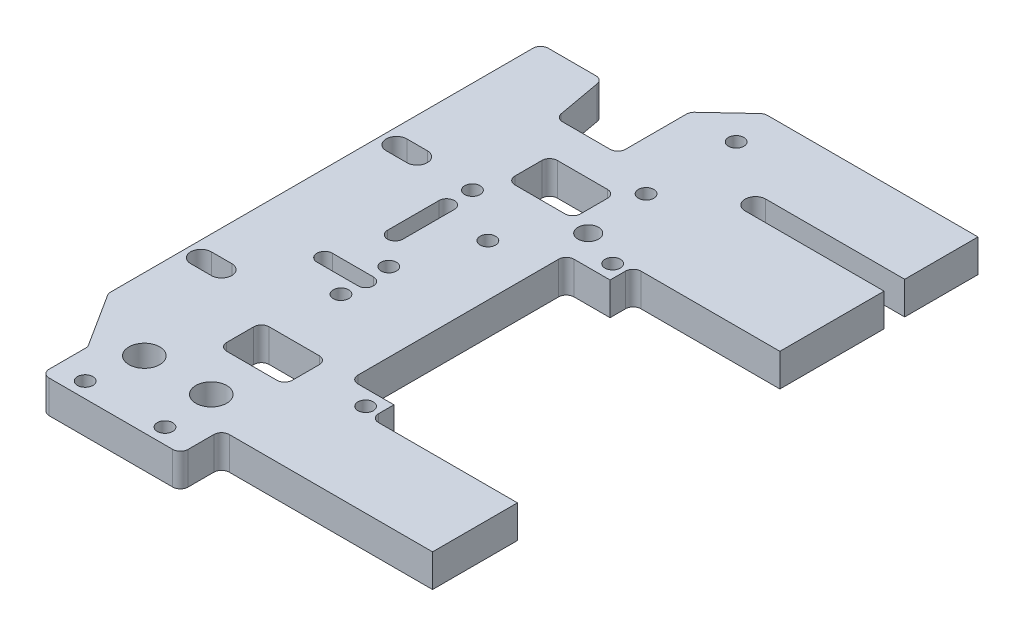
SolidWorks part; units mm, degrees
material "1060 Alloy"
ref_plane "Front Plane" through (0, 0, 0) normal (0, 0, 1) x (1, 0, 0)
ref_plane "Top Plane" through (0, 0, 0) normal (0, 1, 0) x (1, 0, 0)
ref_plane "Right Plane" through (0, 0, 0) normal (1, 0, 0) x (0, 0, -1)
sketch "Sketch1" plane through (0, 0, 0) normal (0, 1, 0) x (1, 0, 0)
  line L0 (48, 228) -> (48, 71.7384) construction
  line L2 (0, 20) -> (0, 104)
  line L4 (96, 20) -> (96, 104)
  line L5 (33.5, 114) -> (26, 107)
  line L6 (26, 107) -> (26, 93)
  line L7 (26, 93) -> (14, 93)
  line L8 (14, 93) -> (12, 104)
  line L9 (12, 104) -> (0, 104)
  line L10 (62.5, 114) -> (70, 107)
  line L11 (70, 107) -> (70, 93)
  line L12 (70, 93) -> (82, 93)
  line L13 (82, 93) -> (84, 104)
  line L14 (84, 104) -> (96, 104)
  line L15 (33.5, 114) -> (62.5, 114)
  line L16 (0, 20) -> (7, 9)
  line L17 (7, 9) -> (7, 0)
  line L18 (89, 9) -> (89, 0)
  line L19 (96, 20) -> (89, 9)
  line L20 (7, 0) -> (34, 0)
  line L21 (34, 0) -> (34, 8)
  line L22 (34, 8) -> (62, 8)
  line L23 (89, 0) -> (62, 0)
  line L24 (62, 0) -> (62, 8)
  line L25 (76.25, 21.75) -> (63.5, 21.75)
  line L26 (19.75, 30) -> (32.5, 30)
  line L27 (19.75, 30) -> (19.75, 21.75)
  line L28 (19.75, 21.75) -> (32.5, 21.75)
  line L29 (32.5, 30) -> (32.5, 21.75)
  line L30 (63.5, 30) -> (63.5, 21.75)
  line L31 (76.25, 30) -> (63.5, 30)
  line L32 (76.25, 30) -> (76.25, 21.75)
  line L33 (0, 53.875) -> (96, 53.875) construction
  line L34 (76.25, 77.75) -> (76.25, 86)
  line L35 (76.25, 77.75) -> (63.5, 77.75)
  line L36 (63.5, 77.75) -> (63.5, 86)
  line L37 (76.25, 86) -> (63.5, 86)
  line L38 (19.75, 86) -> (32.5, 86)
  line L39 (32.5, 77.75) -> (32.5, 86)
  line L40 (19.75, 77.75) -> (32.5, 77.75)
  line L41 (19.75, 77.75) -> (19.75, 86)
  line L42 (3, 75) -> (7, 75)
  line L43 (3, 71) -> (7, 71)
  line L44 (93, 75) -> (89, 75)
  line L45 (93, 71) -> (89, 71)
  line L46 (0, 54) -> (96, 54) construction
  line L47 (93, 37) -> (89, 37)
  line L48 (93, 33) -> (89, 33)
  line L49 (3, 33) -> (7, 33)
  line L50 (3, 37) -> (7, 37)
  line L51 (15, 48.5252) -> (23, 48.5252)
  line L52 (23, 45.5252) -> (15, 45.5252)
  line L53 (81, 48.5252) -> (73, 48.5252)
  line L54 (73, 45.5252) -> (81, 45.5252)
  line L55 (16.5, 67.75) -> (16.5, 57.75)
  line L56 (19.5, 67.75) -> (19.5, 57.75)
  line L57 (76.5, 67.75) -> (76.5, 57.75)
  line L58 (79.5, 67.75) -> (79.5, 57.75)
  line L59 (46.5, 29) -> (38, 29)
  line L60 (38, 29) -> (38, 71)
  line L61 (38, 71) -> (46.5, 71)
  line L62 (46.5, 29) -> (46.5, 26)
  line L63 (18.7278, 50) -> (57.2722, 50) construction
  line L64 (46.5, 71) -> (46.5, 74)
  line L65 (49.5, 29) -> (49.5, 26)
  line L66 (49.5, 29) -> (58, 29)
  line L67 (58, 29) -> (58, 71)
  line L68 (49.5, 71) -> (49.5, 74)
  line L69 (58, 71) -> (49.5, 71)
  line L70 (35.5, 106.5) -> (60.5, 89) construction
  circle A0 centre (12.5, 3) radius 1.5
  circle A1 centre (28, 3) radius 1.5
  circle A2 centre (68, 3) radius 1.5
  circle A3 centre (83.5, 3) radius 1.5
  circle A4 centre (14, 13) radius 3
  circle A5 centre (27, 13) radius 3
  circle A6 centre (69, 13) radius 3
  circle A7 centre (82, 13) radius 3
  arc A8 (3, 75) -> (3, 71) centre (3, 73) ccw
  arc A10 (7, 71) -> (7, 75) centre (7, 73) ccw
  arc A11 (89, 71) -> (89, 75) centre (89, 73) cw
  arc A12 (93, 75) -> (93, 71) centre (93, 73) cw
  arc A13 (93, 33) -> (93, 37) centre (93, 35) ccw
  arc A14 (89, 37) -> (89, 33) centre (89, 35) ccw
  arc A15 (7, 37) -> (7, 33) centre (7, 35) cw
  arc A16 (3, 33) -> (3, 37) centre (3, 35) cw
  circle A17 centre (22.75, 42.455) radius 1.5
  arc A18 (23, 45.5252) -> (23, 48.5252) centre (23, 47.0252) ccw
  arc A19 (15, 48.5252) -> (15, 45.5252) centre (15, 47.0252) ccw
  circle A20 centre (22.75, 51.7511) radius 1.5
  circle A21 centre (73.25, 42.455) radius 1.5
  arc A22 (73, 45.5252) -> (73, 48.5252) centre (73, 47.0252) cw
  arc A23 (81, 48.5252) -> (81, 45.5252) centre (81, 47.0252) cw
  circle A24 centre (73.25, 51.7511) radius 1.5
  circle A25 centre (18, 72.75) radius 1.5
  arc A26 (19.5, 67.75) -> (16.5, 67.75) centre (18, 67.75) ccw
  arc A27 (16.5, 57.75) -> (19.5, 57.75) centre (18, 57.75) ccw
  circle A28 centre (28, 65.75) radius 1.5
  circle A29 centre (68, 65.75) radius 1.5
  circle A30 centre (78, 72.75) radius 1.5
  arc A31 (79.5, 57.75) -> (76.5, 57.75) centre (78, 57.75) cw
  arc A32 (76.5, 67.75) -> (79.5, 67.75) centre (78, 67.75) cw
  circle A33 centre (36.5, 76.75) radius 2
  circle A34 centre (59.5, 76.75) radius 2
  circle A35 centre (35.5, 89) radius 1.5
  circle A36 centre (35.5, 106.5) radius 1.5
  circle A37 centre (60.5, 89) radius 1.5
  circle A38 centre (60.5, 106.5) radius 1.5
  arc A39 (46.5, 26) -> (49.5, 26) centre (48, 26) ccw
  arc A40 (46.5, 74) -> (49.5, 74) centre (48, 74) cw
  circle A41 centre (44, 26) radius 1.5
  circle A42 centre (52, 26) radius 1.5
  circle A43 centre (52, 74) radius 1.5
  circle A44 centre (44, 74) radius 1.5
  circle A45 centre (48, 97.75) radius 2
  point P8 (48, 149.8692)
  point P28 (48, 8)
  point P150 (38, 50)
  dimension "D13" = 3
  dimension "D14" = 3
  dimension "D15" = 5.5
  dimension "D16" = 6
  dimension "D17" = 3
  dimension "D18" = 6
  dimension "D19" = 13
  dimension "D20" = 14
  dimension "D21" = 13
  dimension "D27" = 4
  dimension "D28" = 4
  dimension "D29" = 4
  dimension "D30" = 31
  dimension "D32" = 3
  dimension "D34" = 3
  dimension "D35" = 3
  dimension "D36" = 22.75
  dimension "D37" = 3
  dimension "D39" = 15
  dimension "D40" = 3
  dimension "D41" = 11
  dimension "D42" = 5
  dimension "D43" = 5
  dimension "D44" = 10
  dimension "D45" = 3
  dimension "D46" = 10
  dimension "D47" = 7
  dimension "D48" = 4
  dimension "D49" = 4
  dimension "D50" = 1
  dimension "D51" = 3
  dimension "D52" = 3
  dimension "D53" = 3
  dimension "D54" = 17.5
  dimension "D55" = 21
  dimension "D60" = 3
  dimension "D61" = 3
  dimension "D58" = 3
  dimension "D62" = 4
  dimension "D63" = 4
  dimension "D1" = 10
  dimension "D2" = 96
  dimension "D3" = 12
  dimension "D4" = 21
  dimension "D5" = 7
  dimension "D6" = 7.5
  dimension "D7" = 12
  dimension "D8" = 2
  dimension "D9" = 27
  dimension "D10" = 7
  dimension "D11" = 9
  dimension "D12" = 8
  dimension "D22" = 8.25
  dimension "D23" = 12.75
  dimension "D24" = 21.75
  dimension "D25" = 19.75
  dimension "D26" = 23.875
  dimension "D31" = 114
  dimension "D33" = 17
  dimension "D38" = 8
  dimension "D56" = 42
  dimension "D57" = 38
  dimension "D59" = 1.5
extrude "Boss-Extrude1" add sketch "Sketch1" along normal blind 6.35
fillet "Fillet1" radius 1.5 42 edges at (38, 3.175, -29) (58, 3.175, -71) (63.5, 3.175, -30) (63.5, 3.175, -86) (32.5, 3.175, -86) (32.5, 3.175, -30) (76.25, 3.175, -30) (76.25, 3.175, -86) (19.75, 3.175, -77.75) (63.5, 3.175, -77.75) (63.5, 3.175, -21.75) (19.75, 3.175, -21.75) (32.5, 3.175, -21.75) (32.5, 3.175, -77.75) (76.25, 3.175, -77.75) (58, 3.175, -29) (76.25, 3.175, -21.75) (0, 3.175, -104) (12, 3.175, -104) (14, 3.175, -93) (26, 3.175, -93) (26, 3.175, -107) (33.5, 3.175, -114) (62.5, 3.175, -114) (70, 3.175, -107) (70, 3.175, -93) (82, 3.175, -93) (84, 3.175, -104) (96, 3.175, -104) (96, 3.175, -20) (89, 3.175, -9) (89, 3.175, 0) (62, 3.175, -8) (62, 3.175, 0) (19.75, 3.175, -86) (38, 3.175, -71) (19.75, 3.175, -30) (34, 3.175, -8) (34, 3.175, 0) (0, 3.175, -20) (7, 3.175, -9) (7, 3.175, 0)
ref_plane "Plane1" through (48, 0, 0) normal (1, 0, 0) x (0, 0, -1)
sketch "Sketch3" plane through (48, 0, 0) normal (1, 0, 0) x (0, 0, -1)
  line L1 (-6.4167, 7.5787) -> (123.2615, 7.5787)
  line L2 (-6.4167, 7.5787) -> (-6.4167, -5.6973)
  line L3 (-6.4167, -5.6973) -> (123.2615, -5.6973)
  line L4 (123.2615, 7.5787) -> (123.2615, -5.6973)
extrude "Cut-Extrude1" cut sketch "Sketch3" along normal blind 56
sketch "Sketch4" plane through (48, 0, 0) normal (1, 0, 0) x (0, 0, -1)
  line L4 (114, 0) -> (114, 6.35)
  line L5 (114, 6.35) -> (99.75, 6.35)
  line L6 (99.75, 6.35) -> (99.75, 0)
  line L7 (99.75, 0) -> (114, 0)
  line L8 (114, 0) -> (114, 6.35)
  line L9 (114, 6.35) -> (99.75, 6.35)
  line L10 (99.75, 6.35) -> (99.75, 0)
  line L11 (99.75, 0) -> (114, 0)
  line L12 (75.5, 0) -> (95.75, 0)
  line L13 (95.75, 0) -> (95.75, 6.35)
  line L14 (95.75, 6.35) -> (75.5, 6.35)
  line L15 (75.5, 6.35) -> (75.5, 0)
  line L16 (75.5, 0) -> (95.75, 0)
  line L17 (95.75, 0) -> (95.75, 6.35)
  line L18 (95.75, 6.35) -> (75.5, 6.35)
  line L19 (75.5, 6.35) -> (75.5, 0)
  line L28 (8, 6.35) -> (8, 0)
  line L29 (8, 0) -> (24.5, 0)
  line L30 (24.5, 0) -> (24.5, 6.35)
  line L31 (24.5, 6.35) -> (8, 6.35)
  line L32 (8, 6.35) -> (8, 0)
  line L33 (8, 0) -> (24.5, 0)
  line L34 (24.5, 0) -> (24.5, 6.35)
  line L35 (24.5, 6.35) -> (8, 6.35)
  dimension "D1" = 0
  dimension "D2" = 0
  dimension "D4" = 0
extrude "Boss-Extrude2" add sketch "Sketch4" along normal blind 25
mirror "Mirror1" about plane through (73, 0, 0) normal (1, 0, 0) of bodies 103
ref_plane "Plane2" through (75, 0, 0) normal (1, 0, 0) x (0, 0, -1)
sketch "Sketch5" plane through (75, 0, 0) normal (1, 0, 0) x (0, 0, -1)
  line L1 (-24.6869, 38.3801) -> (134.1511, 38.3801)
  line L2 (-24.6869, 38.3801) -> (-24.6869, -30.8448)
  line L3 (-24.6869, -30.8448) -> (134.1511, -30.8448)
  line L4 (134.1511, 38.3801) -> (134.1511, -30.8448)
extrude "Cut-Extrude2" cut sketch "Sketch5" along normal blind 86
sketch "Sketch6" plane through (38, 0, 0) normal (1, 0, 0) x (0, 0, -1)
  line L0 (50, 6.35) -> (50, 0)
  line L2 (69.5, 0) -> (30.5, 0) construction
